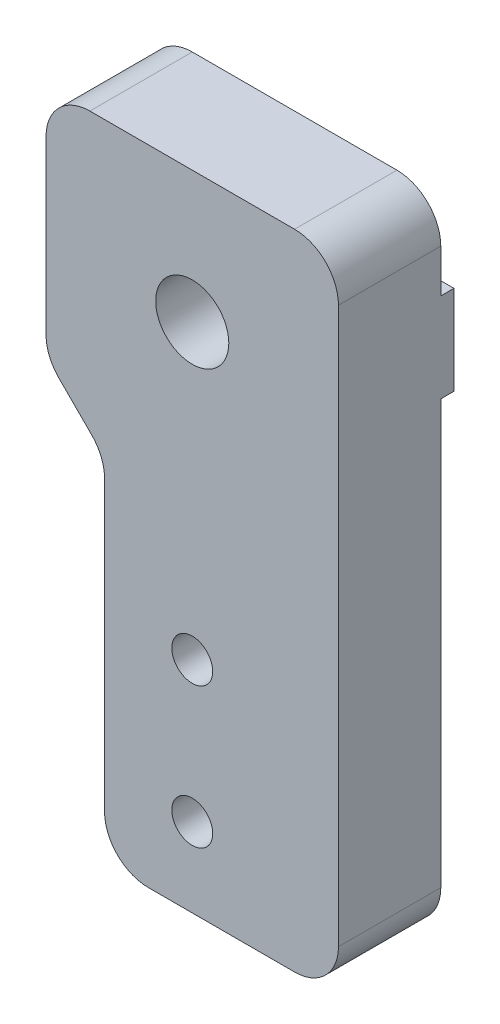
SolidWorks part; units mm, degrees
material "ABS"
ref_plane "Front Plane" through (0, 0, 0) normal (0, 0, 1) x (1, 0, 0)
ref_plane "Top Plane" through (0, 0, 0) normal (0, 1, 0) x (1, 0, 0)
ref_plane "Right Plane" through (0, 0, 0) normal (1, 0, 0) x (0, 0, -1)
sketch "Sketch1" plane through (0, 0, 0) normal (0, 0, 1) x (1, 0, 0)
  line L0 (3, 0) -> (17, 0)
  line L1 (20, 3) -> (20, 41)
  line L2 (10, 0) -> (10, 44) construction
  line L4 (17, 44) -> (3, 44)
  line L5 (0, 41) -> (0, 3)
  line L6 (0, 35) -> (20, 35) construction
  line L8 (10, 0) -> (10, 44) construction
  circle A0 centre (10, 35) radius 2.5
  arc A1 (20, 41) -> (17, 44) centre (17, 41) ccw
  circle A2 centre (10, 5.4) radius 1.4
  circle A3 centre (10, 15) radius 1.4
  arc A7 (3, 44) -> (0, 41) centre (3, 41) ccw
  arc A8 (0, 3) -> (3, 0) centre (3, 3) ccw
  arc A9 (17, 0) -> (20, 3) centre (17, 3) ccw
  point P32 (0, 44)
  point P35 (0, 0)
  point P38 (20, 0)
  dimension "D5" = 5
  dimension "D6" = 10
  dimension "D7" = 10
  dimension "D10" = 2.8
  dimension "D11" = 2.8
  dimension "D12" = 5.4
  dimension "D13" = 9.6
  dimension "D3" = 3
  dimension "D4" = 3
  dimension "D1" = 44
  dimension "D2" = 20
  dimension "D9" = 9
extrude "Boss-Extrude1" add sketch "Sketch1" along normal blind 7
sketch "Sketch2" plane through (20, 0, 0) normal (1, 0, 0) x (0, 0, -1)
  line L1 (0, 38.05) -> (0.9, 38.05)
  line L2 (0, 38.05) -> (0, 31.95)
  line L3 (0, 31.95) -> (0.9, 31.95)
  line L4 (0.9, 38.05) -> (0.9, 31.95)
  line L6 (0, 3) -> (0, 41) construction
  line L7 (0.9, 35) -> (0, 35) construction
  dimension "D1" = 6.1
  dimension "D2" = 0.9
extrude "Boss-Extrude2" add sketch "Sketch2" against normal up to surface (20 mm away) contours L3 L4 L1 L2 up to face at (0, 22, 3.5)
sketch "Sketch3" plane through (0, 0, 0) normal (0, 0, 1) x (1, 0, 0)
  circle A0 centre (10, 35) radius 2.5 construction
  circle A2 centre (10, 35) radius 2.5
extrude "Cut-Extrude1" cut sketch "Sketch3" against normal up to next
sketch "Sketch4" plane through (0, 0, 7) normal (0, 0, 1) x (1, 0, 0)
  line L0 (0, 28) -> (4, 24)
  line L1 (0, 41) -> (0, 3) construction
  line L2 (4, 24) -> (4, 0)
  line L3 (3, 0) -> (17, 0) construction
  line L4 (0, 28) -> (0, 3)
  line L5 (3, 0) -> (4, 0)
  arc A0 (0, 3) -> (3, 0) centre (3, 3) ccw construction
  arc A1 (0, 3) -> (3, 0) centre (3, 3) ccw
  dimension "D1" = 4
  dimension "D2" = 135
  dimension "D3" = 28
extrude "Cut-Extrude2" cut sketch "Sketch4" against normal up to surface (7 mm away) up to face at (8.3333, 11.4429, 0)
fillet "Fillet1" radius 3 3 edges at (0, 28, 3.5) (4, 24, 3.5) (4, 0, 3.5)
